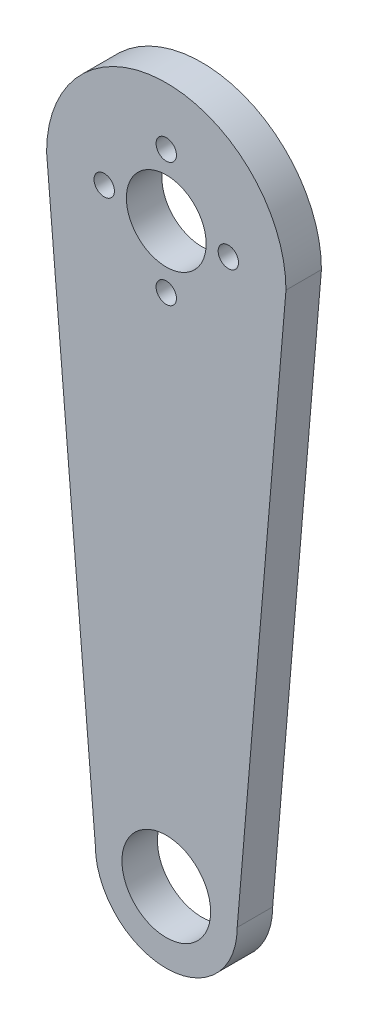
SolidWorks part; units mm, degrees
material "Thornel Mat VMA"
ref_plane "前视基准面" through (0, 0, 0) normal (0, 0, 1) x (1, 0, 0)
ref_plane "上视基准面" through (0, 0, 0) normal (0, 1, 0) x (1, 0, 0)
ref_plane "右视基准面" through (0, 0, 0) normal (1, 0, 0) x (0, 0, -1)
other "Configuration Table"
sketch "草图1" plane through (0, 0, 0) normal (0, 0, 1) x (1, 0, 0)
  line L0 (-13.5, 0) -> (-8, -65)
  line L1 (8, -65) -> (13.5, 0)
  line L2 (0, 0) -> (9.0527, 0) construction
  line L3 (0, 0) -> (0, 5.6003) construction
  arc A0 (13.5, 0) -> (-13.5, 0) centre (0, 0) ccw
  arc A1 (-8, -65) -> (8, -65) centre (0, -65) ccw
  circle A2 centre (0, 0) radius 4.5
  circle A3 centre (0, 0) radius 7 construction
  circle A4 centre (0, 7) radius 1.15
  circle A5 centre (7, 0) radius 1.15
  circle A6 centre (0, -7) radius 1.15
  circle A7 centre (-7, 0) radius 1.15
  circle A28 centre (0, 0) radius 10.5 construction
  circle A49 centre (0, -65) radius 5
  point P50 (0, -20)
  point P69 (0, 0)
  point P76 (0, 0)
  point P78 (0, -39)
  point P79 (0, -36.5)
  point P80 (0, -22.5)
  dimension "D1" = 13.5
  dimension "D2" = 8
  dimension "D4" = 9
  dimension "D5" = 14
  dimension "D6" = 2.3
  dimension "D10" = 21
  dimension "D16" = 10
  dimension "D3" = 65
extrude "凸台-拉伸1" add sketch "草图1" along normal blind 4
